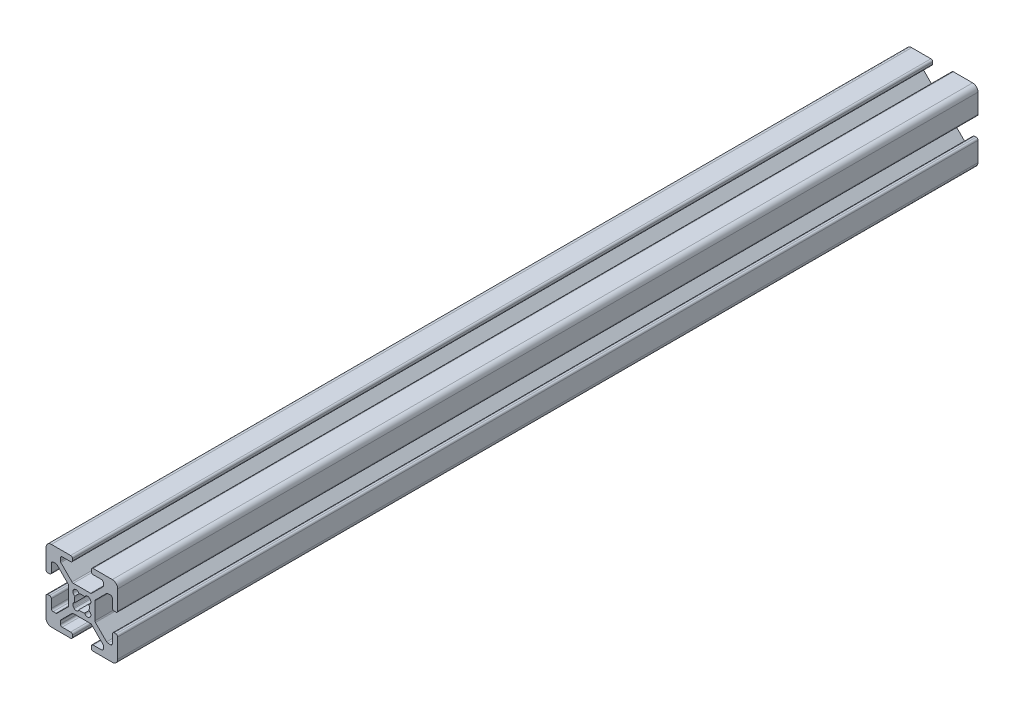
SolidWorks part; units mm, degrees
ref_plane "Front Plane" through (0, 0, 0) normal (0, 0, 1) x (1, 0, 0)
ref_plane "Top Plane" through (0, 0, 0) normal (0, 1, 0) x (1, 0, 0)
ref_plane "Right Plane" through (0, 0, 0) normal (1, 0, 0) x (0, 0, -1)
sketch "Sketch1" plane through (0, 0, 0) normal (0, 0, 1) x (1, 0, 0)
  line B0 (10, 3.138) -> (10, 8.5)
  line B1 (8.5, 10) -> (3.138, 10)
  line B2 (2.63, 9.492) -> (2.63, 9.008)
  line B3 (3.138, 8.5) -> (5.487, 8.5)
  line B4 (5.995, 7.992) -> (5.995, 7.2661)
  line B5 (5.8462, 6.9069) -> (2.7431, 3.8038)
  line B6 (2.3839, 3.655) -> (-2.3839, 3.655)
  line B7 (-2.7431, 3.8038) -> (-5.8462, 6.9069)
  line B8 (-5.995, 7.2661) -> (-5.995, 7.992)
  line B9 (-5.487, 8.5) -> (-3.138, 8.5)
  line B10 (-2.63, 9.008) -> (-2.63, 9.492)
  line B11 (-3.138, 10) -> (-8.5, 10)
  line B12 (-10, 8.5) -> (-10, 3.138)
  line B13 (-9.492, 2.63) -> (-9.008, 2.63)
  line B14 (-8.5, 3.138) -> (-8.5, 5.487)
  line B15 (-7.992, 5.995) -> (-7.2661, 5.995)
  line B16 (-6.9069, 5.8462) -> (-3.8038, 2.7431)
  line B17 (-3.655, 2.3839) -> (-3.655, -2.3839)
  line B18 (-3.8038, -2.7431) -> (-6.9069, -5.8462)
  line B19 (-7.2661, -5.995) -> (-7.992, -5.995)
  line B20 (-8.5, -5.487) -> (-8.5, -3.138)
  line B21 (-9.008, -2.63) -> (-9.492, -2.63)
  line B22 (-10, -3.138) -> (-10, -8.5)
  line B23 (-8.5, -10) -> (-3.138, -10)
  line B24 (-2.63, -9.492) -> (-2.63, -9.008)
  line B25 (-3.138, -8.5) -> (-5.487, -8.5)
  line B26 (-5.995, -7.992) -> (-5.995, -7.2661)
  line B27 (-5.8462, -6.9069) -> (-2.7431, -3.8038)
  line B28 (-2.3839, -3.655) -> (2.3839, -3.655)
  line B29 (2.7431, -3.8038) -> (5.8462, -6.9069)
  line B30 (5.995, -7.2661) -> (5.995, -7.992)
  line B31 (5.487, -8.5) -> (3.138, -8.5)
  line B32 (2.63, -9.008) -> (2.63, -9.492)
  line B33 (3.138, -10) -> (8.5, -10)
  line B34 (10, -8.5) -> (10, -3.138)
  line B35 (9.492, -2.63) -> (9.008, -2.63)
  line B36 (8.5, -3.138) -> (8.5, -5.487)
  line B37 (7.992, -5.995) -> (7.2661, -5.995)
  line B38 (6.9069, -5.8462) -> (3.8038, -2.7431)
  line B39 (3.655, -2.3839) -> (3.655, 2.3839)
  line B40 (3.8038, 2.7431) -> (6.9069, 5.8462)
  line B41 (7.2661, 5.995) -> (7.992, 5.995)
  line B42 (8.5, 5.487) -> (8.5, 3.138)
  line B43 (9.008, 2.63) -> (9.492, 2.63)
  line B44 (-2.1249, -2.3045) -> (-2.3045, -2.1249)
  line B45 (-2.3045, 2.1249) -> (-2.1249, 2.3045)
  line B46 (2.1249, 2.3045) -> (2.3045, 2.1249)
  line B47 (2.3045, -2.1249) -> (2.1249, -2.3045)
  arc B48 (9.492, 2.63) -> (10, 3.138) centre (9.492, 3.138) ccw
  arc B49 (10, 8.5) -> (8.5, 10) centre (8.5, 8.5) ccw
  arc B50 (3.138, 10) -> (2.63, 9.492) centre (3.138, 9.492) ccw
  arc B51 (2.63, 9.008) -> (3.138, 8.5) centre (3.138, 9.008) ccw
  arc B52 (5.487, 8.5) -> (5.995, 7.992) centre (5.487, 7.992) cw
  arc B53 (5.995, 7.2661) -> (5.8462, 6.9069) centre (5.487, 7.2661) cw
  arc B54 (2.7431, 3.8038) -> (2.3839, 3.655) centre (2.3839, 4.163) cw
  arc B55 (-2.3839, 3.655) -> (-2.7431, 3.8038) centre (-2.3839, 4.163) cw
  arc B56 (-5.8462, 6.9069) -> (-5.995, 7.2661) centre (-5.487, 7.2661) cw
  arc B57 (-5.995, 7.992) -> (-5.487, 8.5) centre (-5.487, 7.992) cw
  arc B58 (-3.138, 8.5) -> (-2.63, 9.008) centre (-3.138, 9.008) ccw
  arc B59 (-2.63, 9.492) -> (-3.138, 10) centre (-3.138, 9.492) ccw
  arc B60 (-8.5, 10) -> (-10, 8.5) centre (-8.5, 8.5) ccw
  arc B61 (-10, 3.138) -> (-9.492, 2.63) centre (-9.492, 3.138) ccw
  arc B62 (-9.008, 2.63) -> (-8.5, 3.138) centre (-9.008, 3.138) ccw
  arc B63 (-8.5, 5.487) -> (-7.992, 5.995) centre (-7.992, 5.487) cw
  arc B64 (-7.2661, 5.995) -> (-6.9069, 5.8462) centre (-7.2661, 5.487) cw
  arc B65 (-3.8038, 2.7431) -> (-3.655, 2.3839) centre (-4.163, 2.3839) cw
  arc B66 (-3.655, -2.3839) -> (-3.8038, -2.7431) centre (-4.163, -2.3839) cw
  arc B67 (-6.9069, -5.8462) -> (-7.2661, -5.995) centre (-7.2661, -5.487) cw
  arc B68 (-7.992, -5.995) -> (-8.5, -5.487) centre (-7.992, -5.487) cw
  arc B69 (-8.5, -3.138) -> (-9.008, -2.63) centre (-9.008, -3.138) ccw
  arc B70 (-9.492, -2.63) -> (-10, -3.138) centre (-9.492, -3.138) ccw
  arc B71 (-10, -8.5) -> (-8.5, -10) centre (-8.5, -8.5) ccw
  arc B72 (-3.138, -10) -> (-2.63, -9.492) centre (-3.138, -9.492) ccw
  arc B73 (-2.63, -9.008) -> (-3.138, -8.5) centre (-3.138, -9.008) ccw
  arc B74 (-5.487, -8.5) -> (-5.995, -7.992) centre (-5.487, -7.992) cw
  arc B75 (-5.995, -7.2661) -> (-5.8462, -6.9069) centre (-5.487, -7.2661) cw
  arc B76 (-2.7431, -3.8038) -> (-2.3839, -3.655) centre (-2.3839, -4.163) cw
  arc B77 (2.3839, -3.655) -> (2.7431, -3.8038) centre (2.3839, -4.163) cw
  arc B78 (5.8462, -6.9069) -> (5.995, -7.2661) centre (5.487, -7.2661) cw
  arc B79 (5.995, -7.992) -> (5.487, -8.5) centre (5.487, -7.992) cw
  arc B80 (3.138, -8.5) -> (2.63, -9.008) centre (3.138, -9.008) ccw
  arc B81 (2.63, -9.492) -> (3.138, -10) centre (3.138, -9.492) ccw
  arc B82 (8.5, -10) -> (10, -8.5) centre (8.5, -8.5) ccw
  arc B83 (10, -3.138) -> (9.492, -2.63) centre (9.492, -3.138) ccw
  arc B84 (9.008, -2.63) -> (8.5, -3.138) centre (9.008, -3.138) ccw
  arc B85 (8.5, -5.487) -> (7.992, -5.995) centre (7.992, -5.487) cw
  arc B86 (7.2661, -5.995) -> (6.9069, -5.8462) centre (7.2661, -5.487) cw
  arc B87 (3.8038, -2.7431) -> (3.655, -2.3839) centre (4.163, -2.3839) cw
  arc B88 (3.655, 2.3839) -> (3.8038, 2.7431) centre (4.163, 2.3839) cw
  arc B89 (6.9069, 5.8462) -> (7.2661, 5.995) centre (7.2661, 5.487) cw
  arc B90 (7.992, 5.995) -> (8.5, 5.487) centre (7.992, 5.487) cw
  arc B91 (8.5, 3.138) -> (9.008, 2.63) centre (9.008, 3.138) ccw
  arc B92 (0.804, -1.9351) -> (-0.804, -1.9351) centre (0, 0) cw
  arc B93 (-0.804, -1.9351) -> (-2.1249, -2.3045) centre (-1.5684, -1.748) cw
  arc B94 (-2.3045, -2.1249) -> (-1.9351, -0.804) centre (-1.748, -1.5684) cw
  arc B95 (-1.9351, -0.804) -> (-1.9351, 0.804) centre (0, 0) cw
  arc B96 (-1.9351, 0.804) -> (-2.3045, 2.1249) centre (-1.748, 1.5684) cw
  arc B97 (-2.1249, 2.3045) -> (-0.804, 1.9351) centre (-1.5684, 1.748) cw
  arc B98 (-0.804, 1.9351) -> (0.804, 1.9351) centre (0, 0) cw
  arc B99 (0.804, 1.9351) -> (2.1249, 2.3045) centre (1.5684, 1.748) cw
  arc B100 (2.3045, 2.1249) -> (1.9351, 0.804) centre (1.748, 1.5684) cw
  arc B101 (1.9351, 0.804) -> (1.9351, -0.804) centre (0, 0) cw
  arc B102 (1.9351, -0.804) -> (2.3045, -2.1249) centre (1.748, -1.5684) cw
  arc B103 (2.1249, -2.3045) -> (0.804, -1.9351) centre (1.5684, -1.748) cw
sketch_block_instance "Block1-1"
sketch_block "Block1"
extrude "Boss-Extrude1" add sketch "Sketch1" against normal mid plane 240
